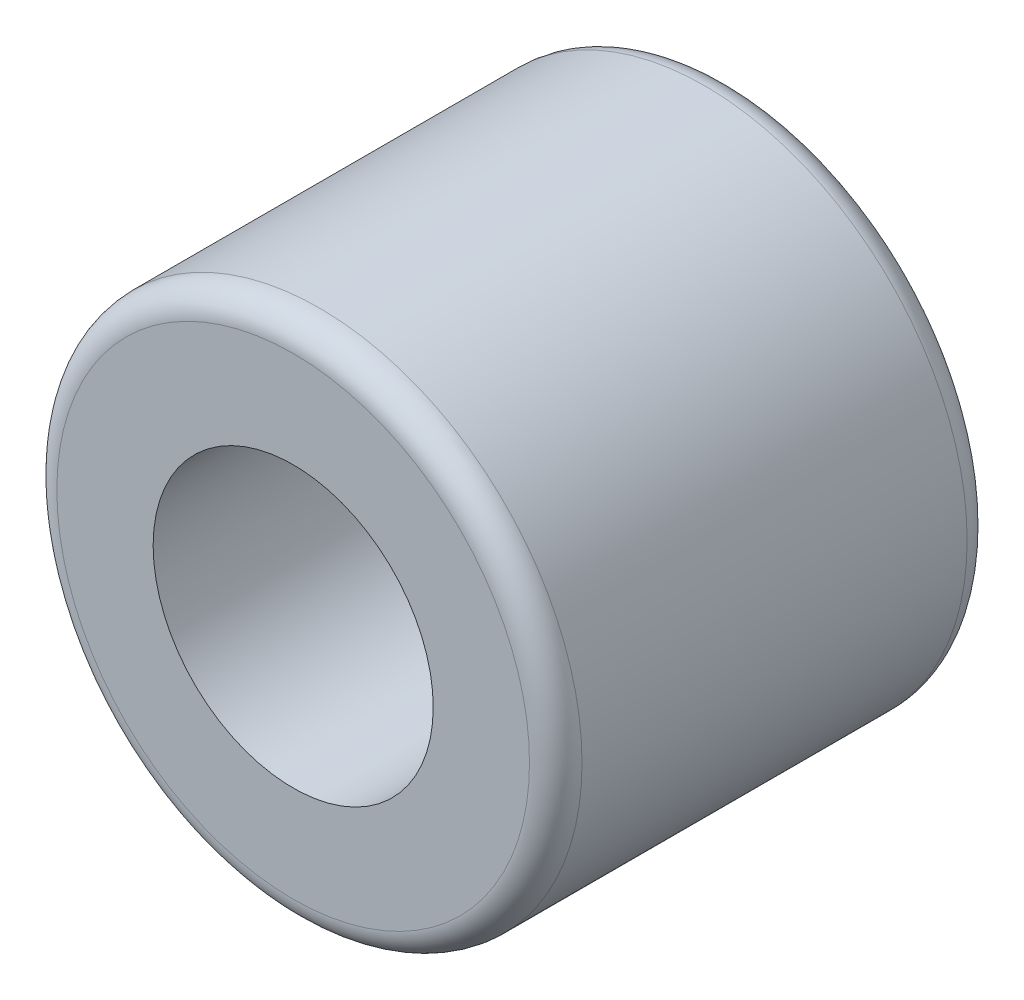
SolidWorks part; units mm, degrees
ref_plane "Front Plane" through (0, 0, 0) normal (0, 0, 1) x (1, 0, 0)
ref_plane "Top Plane" through (0, 0, 0) normal (0, 1, 0) x (1, 0, 0)
ref_plane "Right Plane" through (0, 0, 0) normal (1, 0, 0) x (0, 0, -1)
sketch "Sketch1" plane through (0, 0, 0) normal (0, 0, 1) x (1, 0, 0)
  circle A0 centre (0, 0) radius 3
  circle A1 centre (0, 0) radius 1.6
  dimension "D1" = 6
  dimension "D2" = 3.2
extrude "Boss-Extrude1" add sketch "Sketch1" along normal blind 5
fillet "Fillet1" radius 0.3 2 edges at (3, 0, 0) (3, 0, 5)
